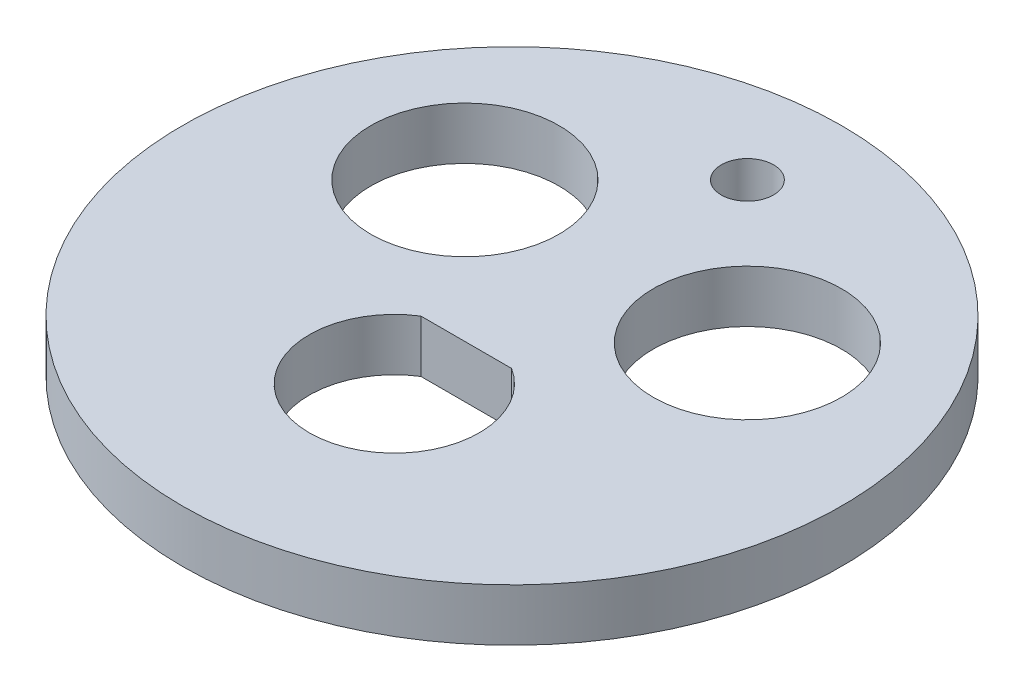
SolidWorks part; units mm, degrees
ref_plane "Front Plane" through (0, 0, 0) normal (0, 0, 1) x (1, 0, 0)
ref_plane "Top Plane" through (0, 0, 0) normal (0, 1, 0) x (1, 0, 0)
ref_plane "Right Plane" through (0, 0, 0) normal (1, 0, 0) x (0, 0, -1)
sketch "Sketch1" plane through (0, 0, 0) normal (0, 0, 1) x (1, 0, 0)
  line L0 (0, -200) -> (0, 100) construction
  line L1 (0, 0) -> (0, 2)
  line L2 (0, 2) -> (12.6, 2)
  line L3 (12.6, 2) -> (12.6, 0)
  line L4 (12.6, 0) -> (0, 0)
revolve "Revolve1" add sketch "Sketch1" angle 360 about L0
sketch "SMA D6.5 - hoses D7.2 - vent D2" plane through (0, 0, 0) normal (0, 1, 0) x (1, 0, 0)
  line L0 (-1.7321, -1.75) -> (1.7321, -1.75)
  arc A0 (1.7321, -1.75) -> (-1.7321, -1.75) centre (0, -4.5) cw
  circle A1 centre (-5.4, 3.6) radius 3.6
  circle A2 centre (5.4, 3.6) radius 3.6
  circle A3 centre (0, 9) radius 1
extrude "Four through holes - both directions" cut sketch "SMA D6.5 - hoses D7.2 - vent D2" against normal through all and the other way through all
